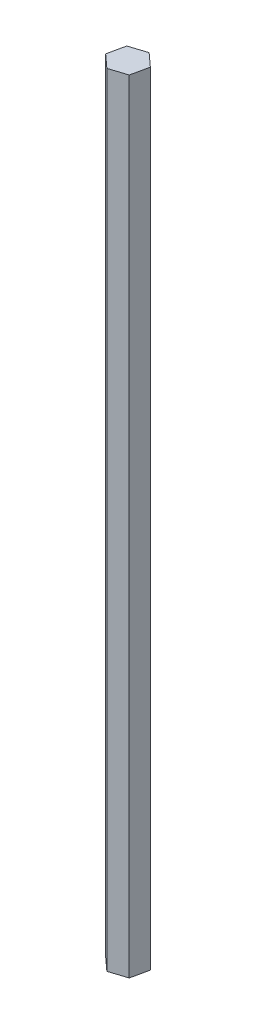
SolidWorks part; units mm, degrees
ref_plane "Front Plane" through (0, 0, 0) normal (0, 0, 1) x (1, 0, 0)
ref_plane "Top Plane" through (0, 0, 0) normal (0, 1, 0) x (1, 0, 0)
ref_plane "Right Plane" through (0, 0, 0) normal (1, 0, 0) x (0, 0, -1)
sketch "Sketch2" plane through (0, 0, 0) normal (0, 1, 0) x (1, 0, 0)
  line L1 (2.1373, -1.9404) -> (2.7491, 0.8807)
  line L2 (2.7491, 0.8807) -> (0.6118, 2.8212)
  line L3 (0.6118, 2.8212) -> (-2.1373, 1.9404)
  line L4 (-2.1373, 1.9404) -> (-2.7491, -0.8807)
  line L5 (-2.7491, -0.8807) -> (-0.6118, -2.8212)
  line L6 (-0.6118, -2.8212) -> (2.1373, -1.9404)
  circle A0 centre (0, 0) radius 2.5 construction
extrude "Boss-Extrude1" add sketch "Sketch2" along normal blind 127
